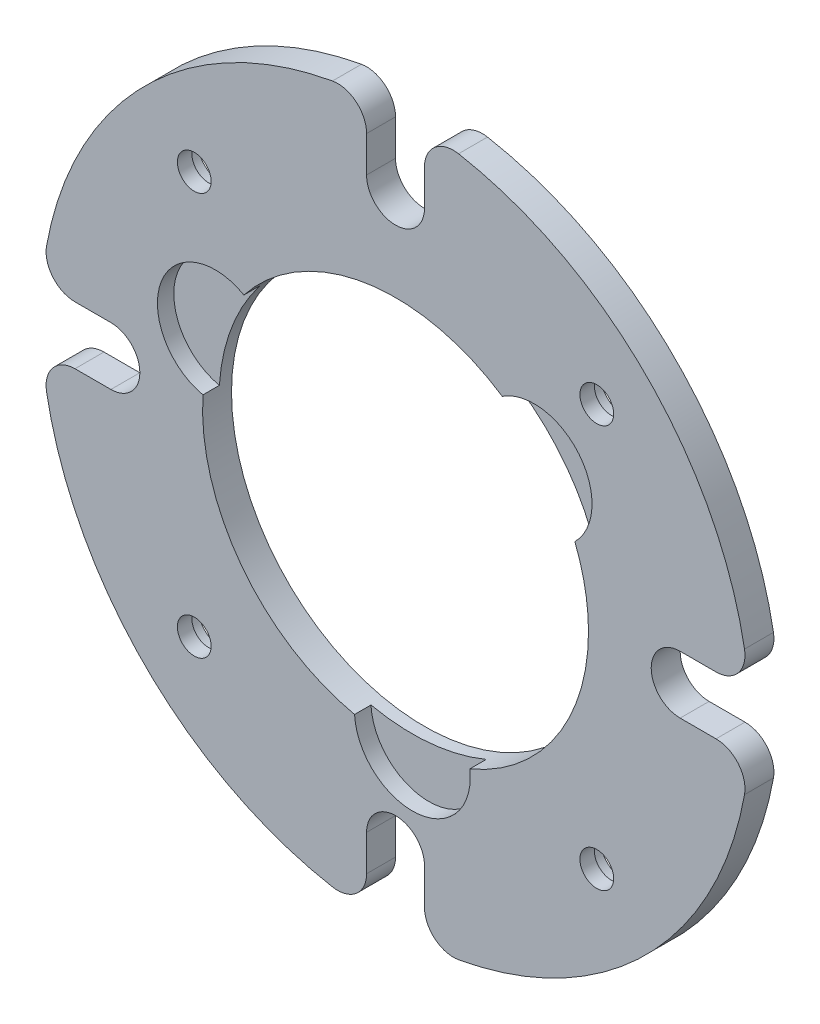
SolidWorks part; units mm, degrees
ref_plane "Спереди" through (0, 0, 0) normal (0, 0, 1) x (1, 0, 0)
ref_plane "Сверху" through (0, 0, 0) normal (0, 1, 0) x (1, 0, 0)
ref_plane "Справа" through (0, 0, 0) normal (1, 0, 0) x (0, 0, -1)
sketch "Sketch1" plane through (0, 0, 0) normal (0, 0, 1) x (1, 0, 0)
  line L0 (3.9, 6.755) -> (7.8, 0) construction
  line L2 (5.85, 10.1325) -> (11.7, 0) construction
  line L4 (7.8, 13.51) -> (15.6, 0) construction
  circle A61 centre (0, 0) radius 20
  circle A131 centre (0, 0) radius 1.25
  circle A484 centre (3.9, 0) radius 1.25
  circle A485 centre (7.8, 0) radius 1.25
  circle A486 centre (11.7, 0) radius 1.25
  circle A487 centre (15.6, 0) radius 1.25
  circle A488 centre (1.95, -3.3775) radius 1.25
  circle A489 centre (3.9, -6.755) radius 1.25
  circle A490 centre (5.85, -10.1325) radius 1.25
  circle A491 centre (7.8, -13.51) radius 1.25
  circle A492 centre (-1.95, -3.3775) radius 1.25
  circle A493 centre (-3.9, -6.755) radius 1.25
  circle A494 centre (-5.85, -10.1325) radius 1.25
  circle A495 centre (-7.8, -13.51) radius 1.25
  circle A496 centre (-3.9, 0) radius 1.25
  circle A497 centre (-7.8, 0) radius 1.25
  circle A498 centre (-11.7, 0) radius 1.25
  circle A499 centre (-15.6, 0) radius 1.25
  circle A500 centre (-1.95, 3.3775) radius 1.25
  circle A501 centre (-3.9, 6.755) radius 1.25
  circle A502 centre (-5.85, 10.1325) radius 1.25
  circle A503 centre (-7.8, 13.51) radius 1.25
  circle A504 centre (1.95, 3.3775) radius 1.25
  circle A505 centre (3.9, 6.755) radius 1.25
  circle A506 centre (5.85, 10.1325) radius 1.25
  circle A507 centre (7.8, 13.51) radius 1.25
  circle A508 centre (5.85, 3.3775) radius 1.25
  circle A509 centre (7.8, 6.755) radius 1.25
  circle A510 centre (9.75, 3.3775) radius 1.25
  circle A511 centre (11.7, 6.755) radius 1.25
  circle A512 centre (9.7491, 10.1341) radius 1.25
  circle A513 centre (13.6509, 3.3759) radius 1.25
  circle A514 centre (5.85, -3.3791) radius 1.25
  circle A515 centre (9.75, -3.3791) radius 1.25
  circle A516 centre (7.8, -6.7566) radius 1.25
  circle A517 centre (11.7, -6.7566) radius 1.25
  circle A518 centre (9.7491, -10.1356) radius 1.25
  circle A519 centre (13.6509, -3.3775) radius 1.25
  circle A520 centre (-0.0013, -6.7573) radius 1.25
  circle A521 centre (1.9487, -10.1348) radius 1.25
  circle A522 centre (-1.9513, -10.1348) radius 1.25
  circle A523 centre (-0.0013, -13.5123) radius 1.25
  circle A524 centre (-3.9032, -13.5123) radius 1.25
  circle A525 centre (3.9005, -13.5123) radius 1.25
  circle A526 centre (-5.8527, -3.3791) radius 1.25
  circle A527 centre (-7.8027, -6.7566) radius 1.25
  circle A528 centre (-9.7527, -3.3791) radius 1.25
  circle A529 centre (-11.7027, -6.7566) radius 1.25
  circle A530 centre (-13.6536, -3.3775) radius 1.25
  circle A531 centre (-9.7518, -10.1356) radius 1.25
  circle A532 centre (-5.8527, 3.3775) radius 1.25
  circle A533 centre (-9.7527, 3.3775) radius 1.25
  circle A534 centre (-7.8027, 6.755) radius 1.25
  circle A535 centre (-11.7027, 6.755) radius 1.25
  circle A536 centre (-9.7518, 10.1341) radius 1.25
  circle A537 centre (-13.6536, 3.3759) radius 1.25
  circle A538 centre (-0.0014, 6.7558) radius 1.25
  circle A539 centre (-1.9514, 10.1333) radius 1.25
  circle A540 centre (1.9486, 10.1333) radius 1.25
  circle A541 centre (-0.0014, 13.5108) radius 1.25
  circle A542 centre (3.9005, 13.5108) radius 1.25
  circle A543 centre (-3.9032, 13.5108) radius 1.25
  circle A544 centre (13.65, -1.1258) radius 2.2517 construction
  circle A545 centre (11.7009, -4.5044) radius 2.2522 construction
  circle A546 centre (9.75, -7.8834) radius 2.2522 construction
  circle A547 centre (7.7987, -11.2591) radius 2.2509 construction
  circle A548 centre (13.65, -1.1258) radius 0.65
  circle A549 centre (11.7009, -4.5044) radius 0.65
  circle A550 centre (9.75, -7.8834) radius 0.65
  circle A551 centre (7.7987, -11.2591) radius 0.65
  circle A552 centre (9.75, -1.1258) radius 0.65
  circle A553 centre (7.8009, -4.5044) radius 0.65
  circle A554 centre (5.85, -7.8834) radius 0.65
  circle A555 centre (3.8987, -11.2591) radius 0.65
  circle A556 centre (5.85, -1.1258) radius 0.65
  circle A557 centre (3.9009, -4.5044) radius 0.65
  circle A558 centre (1.95, -7.8834) radius 0.65
  circle A559 centre (-0.0013, -11.2591) radius 0.65
  circle A560 centre (1.95, -1.1258) radius 0.65
  circle A561 centre (0.0009, -4.5044) radius 0.65
  circle A562 centre (-1.95, -7.8834) radius 0.65
  circle A563 centre (-3.9013, -11.2591) radius 0.65
  circle A564 centre (-1.95, -1.1258) radius 0.65
  circle A565 centre (-3.8991, -4.5044) radius 0.65
  circle A566 centre (-5.85, -7.8834) radius 0.65
  circle A567 centre (-7.8013, -11.2591) radius 0.65
  circle A568 centre (-5.85, -1.1258) radius 0.65
  circle A569 centre (-7.7991, -4.5044) radius 0.65
  circle A570 centre (-9.75, -7.8834) radius 0.65
  circle A572 centre (-9.75, -1.1258) radius 0.65
  circle A573 centre (-11.6991, -4.5044) radius 0.65
  circle A576 centre (-13.65, -1.1258) radius 0.65
  circle A580 centre (-15.5991, -4.5044) radius 0.65 [skipped]
  circle A581 centre (-13.65, -7.8834) radius 0.65 [skipped]
  circle A582 centre (-17.55, -7.8834) radius 0.65 [skipped]
  circle A583 centre (-19.5013, -11.2591) radius 0.65 [skipped]
  circle A584 centre (-15.6013, -11.2591) radius 0.65 [skipped]
  circle A585 centre (-11.7013, -11.2591) radius 0.65 [skipped]
  circle A587 centre (0, 2.2517) radius 2.2517 construction
  circle A588 centre (0, 2.2517) radius 0.65
  circle A589 centre (3.9, 2.2517) radius 0.65
  circle A590 centre (7.8, 2.2517) radius 0.65
  circle A591 centre (11.7, 2.2517) radius 0.65
  circle A592 centre (15.6, 2.2517) radius 0.65
  circle A593 centre (1.9491, 5.6297) radius 2.2522 construction
  circle A594 centre (1.9491, 5.6297) radius 0.65
  circle A595 centre (5.8491, 5.6297) radius 0.65
  circle A596 centre (9.7491, 5.6297) radius 0.65
  circle A597 centre (13.6491, 5.6297) radius 0.65
  circle A598 centre (3.8991, 9.0072) radius 2.2522 construction
  circle A599 centre (3.8991, 9.0072) radius 0.65
  circle A600 centre (7.7991, 9.0072) radius 0.65
  circle A601 centre (11.6991, 9.0072) radius 0.65
  circle A602 centre (5.85, 12.3842) radius 2.2517 construction
  circle A603 centre (5.85, 12.3842) radius 0.65
  circle A604 centre (9.75, 12.3842) radius 0.65
  circle A605 centre (5.85, -14.6358) radius 0.65
  circle A606 centre (1.9509, -14.6353) radius 0.65
  circle A607 centre (-1.9491, -14.6353) radius 0.65
  circle A608 centre (-5.85, -14.6358) radius 0.65
  circle A609 centre (-15.6, 2.2517) radius 0.65
  circle A610 centre (-13.65, 5.6281) radius 0.65
  circle A611 centre (-11.7, 9.0056) radius 0.65
  circle A612 centre (-9.75, 12.3842) radius 0.65
  circle A613 centre (-5.85, 12.3842) radius 0.65
  circle A614 centre (-1.95, 12.3842) radius 0.65
  circle A615 centre (1.95, 12.3842) radius 0.65
  circle A616 centre (-7.8, 9.0056) radius 0.65
  circle A617 centre (-9.75, 5.6281) radius 0.65
  circle A618 centre (-11.7, 2.2517) radius 0.65
  circle A619 centre (-3.9, 9.0056) radius 0.65
  circle A620 centre (-5.85, 5.6281) radius 0.65
  circle A621 centre (-7.8, 2.2517) radius 0.65
  circle A622 centre (0, 9.0056) radius 0.65
  circle A623 centre (-1.95, 5.6281) radius 0.65
  circle A624 centre (-3.9, 2.2517) radius 0.65
  point P51 (0, 0)
  point P125 (-0.0013, -0.0008)
  point P231 (0, 0)
  dimension "D1" = 5
  dimension "D3" = 6
  dimension "D5" = 8
  dimension "D7" = 4
  dimension "D2" = 6
  dimension "D6" = 5
  dimension "D8" = 3
  dimension "D9" = 2
  dimension "D4" = 1.3
  dimension "D10" = 3
sketch "Sketch5" plane through (0, 0, 0) normal (0, 0, 1) x (1, 0, 0)
  circle A0 centre (0, 0) radius 25.4054 construction
  circle A1 centre (0, 0) radius 36.7568
  circle A2 centre (0, 0) radius 20
  dimension "D1" = 40
extrude "Boss-Extrude1" add sketch "Sketch5" against normal blind 3
sketch "Sketch8" plane through (0, 0, 0) normal (0, 0, 1) x (1, 0, 0)
  line L0 (0, 0) -> (-19.915, 0)
  line L1 (0, 0) -> (-20.8597, 20.8597) construction
  circle A0 centre (0, 0) radius 29.5 construction
  circle A1 centre (-20.8597, 20.8597) radius 1.75
  circle A2 centre (20.8597, 20.8597) radius 1.75
  circle A3 centre (20.8597, -20.8597) radius 1.75
  circle A4 centre (-20.8597, -20.8597) radius 1.75
  point P15 (0, 0)
  dimension "D1" = 4
extrude "Cut-Extrude3" cut sketch "Sketch8" against normal blind 5 contours A2 | A1 | A4 | A3
sketch "Sketch27" plane through (0, 0, 0) normal (0, 0, 1) x (1, 0, 0)
  circle A0 centre (0, 0) radius 29.5 construction
  circle A1 centre (0, 29.5) radius 1.75
  circle A2 centre (29.5, 0) radius 1.75
  circle A3 centre (0, -29.5) radius 1.75
  circle A4 centre (-29.5, 0) radius 1.75
  point P15 (0, 0)
extrude "Cut-Extrude9" cut sketch "Sketch27" against normal blind 5
sketch "Sketch28" plane through (0, 0, 0) normal (0, 0, 1) x (1, 0, 0)
  line L0 (-3, 29.5) -> (-3, 40.0499)
  line L1 (-3, 40.0499) -> (3, 40.0499)
  line L2 (3, 40.0499) -> (3, 29.5)
  circle A0 centre (0, 29.5) radius 3
  circle M2 centre (0, 29.5) radius 1.75
  circle M11 centre (0, 0) radius 36.7568
extrude "Cut-Extrude10" cut sketch "Sketch28" against normal blind 10 contours A0 M2 | A0 L2 L0 M11 | L2 L1 L0 M11
fillet "Fillet1" radius 3 2 edges at (-3, 36.6341, -1.5) (3, 36.6341, -1.5)
pattern_circular "CirPattern1" count 4 over 360 about axis through (0, 0, 0) along (0, 0, 1) of "Cut-Extrude10", "Fillet1"
sketch "Sketch32" plane through (0, 0, 0) normal (0, 0, 1) x (1, 0, 0)
  circle A1 centre (0, 0) radius 20 construction
  circle A6 centre (0, 0) radius 20
  circle A7 centre (-18.6779, 7.151) radius 6
  circle A8 centre (14.367, 11.655) radius 6
  circle A9 centre (1.7452, -19.2147) radius 6
  point P11 (0, 0)
  point P12 (-0.8552, -0.1362)
  circle M9 centre (0, 0) radius 20
  dimension "D1" = 3
extrude "Cut-Extrude11" cut sketch "Sketch32" against normal blind 1.7 contours A7 M9 | A8 M9 | A9 M9
sketch "Sketch33" plane through (0, 0, -3) normal (0, 0, -1) x (-1, 0, 0)
  circle A0 centre (-20.8597, 20.8597) radius 2.7
  circle A1 centre (20.8597, 20.8597) radius 2.7
  circle A2 centre (20.8597, -20.8597) radius 2.7
  circle A3 centre (-20.8597, -20.8597) radius 2.7
  point P12 (0, 0)
  dimension "D1" = 4
extrude "Cut-Extrude12" cut sketch "Sketch33" against normal blind 1.5
